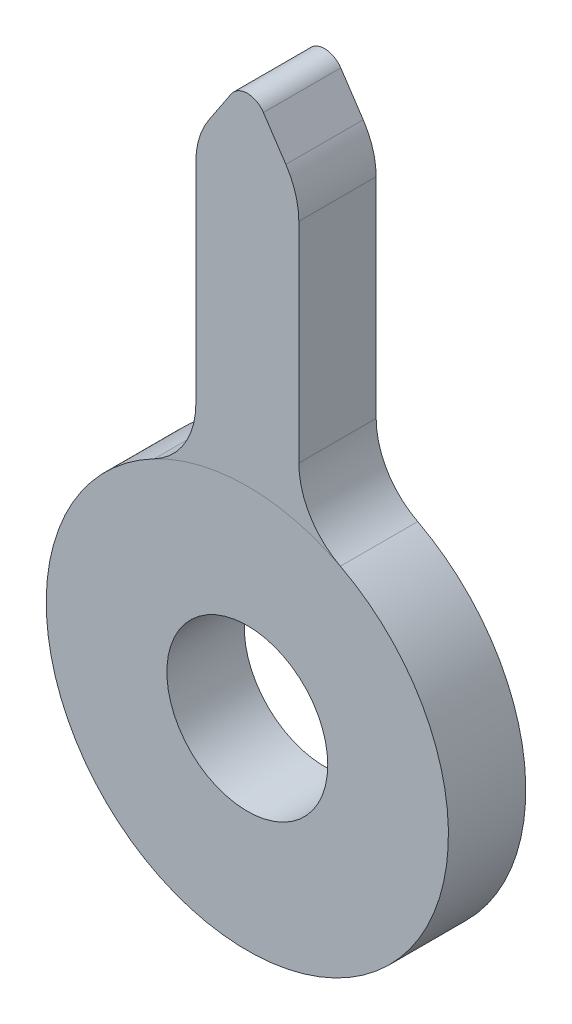
SolidWorks part; units mm, degrees
ref_plane "Front Plane" through (0, 0, 0) normal (0, 0, 1) x (1, 0, 0)
ref_plane "Top Plane" through (0, 0, 0) normal (0, 1, 0) x (1, 0, 0)
ref_plane "Right Plane" through (0, 0, 0) normal (1, 0, 0) x (0, 0, -1)
sketch "Sketch1" plane through (0, 0, 0) normal (0, 0, 1) x (1, 0, 0)
  line L0 (0, 0) -> (0, 11.43) construction
  line L1 (1.0566, 3.99) -> (1.0566, 9.8425)
  line L2 (-1.0566, 3.99) -> (-1.0566, 9.8425)
  line L3 (0, 11.43) -> (-1.0566, 9.8425)
  line L4 (0, 11.43) -> (1.0566, 9.8425)
  line L5 (-1.0566, 0) -> (-1.0566, 11.43) construction
  line L6 (1.0566, 0) -> (1.0566, 11.43) construction
  circle A0 centre (0, 0) radius 1.651
  arc A1 (-1.0566, 3.99) -> (1.0566, 3.99) centre (0, 0) ccw
  dimension "D1" = 3.302
  dimension "D3" = 8.255
  dimension "D2" = 11.43
  dimension "D4" = 1.0566
  dimension "D6" = 1.5875
  dimension "D5" = 1.0566
extrude "Boss-Extrude1" add sketch "Sketch1" along normal blind 1.5875
sketch "Sketch2" plane through (0, 0, 1.5875) normal (0, 0, 1) x (1, 0, 0)
  arc A0 (-1.0566, 3.99) -> (1.0566, 3.99) centre (0, 0) cw
split line "Split Line1"
fillet "Fillet1" radius 1.5875 2 edges at (1.0566, 9.8425, 0.7937) (-1.0566, 9.8425, 0.7937)
fillet "Fillet2" radius 0.3969 1 edges at (0, 11.43, 0.7937)
fillet "Fillet3" radius 1.5875 2 edges at (-1.0566, 3.99, 0.7937) (1.0566, 3.99, 0.7937)
